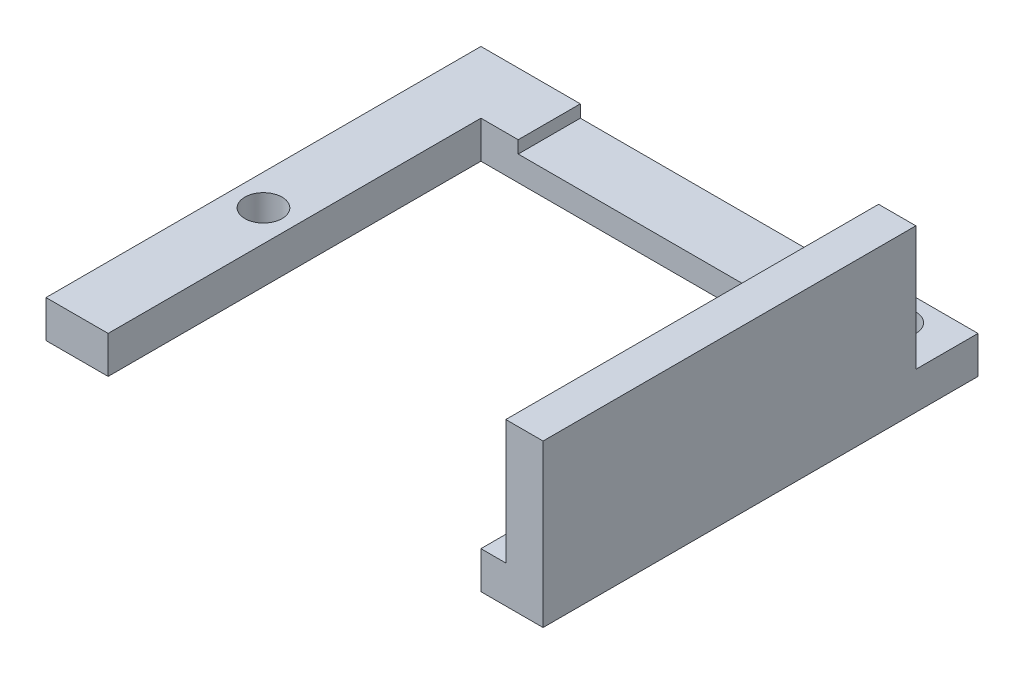
SolidWorks part; units mm, degrees
ref_plane "Front Plane" through (0, 0, 0) normal (0, 0, 1) x (1, 0, 0)
ref_plane "Top Plane" through (0, 0, 0) normal (0, 1, 0) x (1, 0, 0)
ref_plane "Right Plane" through (0, 0, 0) normal (1, 0, 0) x (0, 0, -1)
sketch "Sketch1" plane through (0, 0, 0) normal (0, 1, 0) x (1, 0, 0)
  line L0 (0, 47.9112) -> (0, -41.711) construction
  line L1 (20, -11.8999) -> (15, -11.8999)
  line L2 (-15, 18.1001) -> (-15, -11.8999)
  line L3 (-15, 18.1001) -> (15, 18.1001)
  line L5 (20, 23.1001) -> (-20, 23.1001)
  line L6 (-20, 23.1001) -> (-20, -11.8999)
  line L7 (-20, -11.8999) -> (-15, -11.8999)
  line L8 (20, 23.1001) -> (20, -11.8999)
  line L9 (15, 18.1001) -> (15, -11.8999)
  point P6 (0, 3.1001)
  point P9 (-15, 3.1001)
  point P15 (15, 3.1001)
  dimension "D1" = 20
  dimension "D2" = 15
  dimension "D3" = 20
  dimension "D4" = 15
  dimension "D5" = 18.1001
  dimension "D6" = 3.1001
extrude "Boss-Extrude1" add sketch "Sketch1" along normal blind 3
sketch "Sketch2" plane through (0, 3, 0) normal (0, 1, 0) x (1, 0, 0)
  line L0 (0, 23.1001) -> (0, -12.1589) construction
  line L1 (20, 23.1001) -> (-20, 23.1001) construction
  circle A1 centre (-17.5, 3.1001) radius 1.5
extrude "Cut-Extrude1" cut sketch "Sketch2" against normal up to surface (3 mm away) up to face at (0, 0, -4.3501)
sketch "Sketch3" plane through (0, 3, 0) normal (0, 1, 0) x (1, 0, 0)
  line L0 (12, 18.1001) -> (-12, 18.1001)
  line L1 (-15, 18.1001) -> (15, 18.1001) construction
  line L2 (-12, 18.1001) -> (-12, 23.1001)
  line L3 (20, 23.1001) -> (-20, 23.1001) construction
  line L4 (-12, 23.1001) -> (12, 23.1001)
  line L5 (12, 23.1001) -> (12, 18.1001)
  point P5 (0, 18.1001)
  dimension "D1" = 24
  dimension "D2" = 5
  dimension "D3" = 12
extrude "Cut-Extrude2" cut sketch "Sketch3" against normal blind 1
sketch "Sketch4" plane through (0, 3, 0) normal (0, 1, 0) x (1, 0, 0)
  line L0 (20, -11.8999) -> (20, 18.1001)
  line L1 (20, -11.8999) -> (20, 23.1001) construction
  line L2 (20, 18.1001) -> (17, 18.1001)
  line L3 (17, 18.1001) -> (17, -11.8999)
  line L4 (15, -11.8999) -> (20, -11.8999) construction
  line L5 (17, -11.8999) -> (20, -11.8999)
  dimension "D1" = 30
  dimension "D2" = 3
extrude "Boss-Extrude2" add sketch "Sketch4" along normal blind 10
sketch "Sketch5" plane through (0, 3, 0) normal (0, 1, 0) x (1, 0, 0)
  line L0 (20, 18.1001) -> (20, 23.1001) construction
  circle A0 centre (16, 20.6001) radius 1.5
  dimension "D1" = 3
  dimension "D2" = 20.6001
  dimension "D3" = 4
extrude "Cut-Extrude3" cut sketch "Sketch5" against normal up to surface (3 mm away) up to face at (-17.5, 0, -4.6001)
